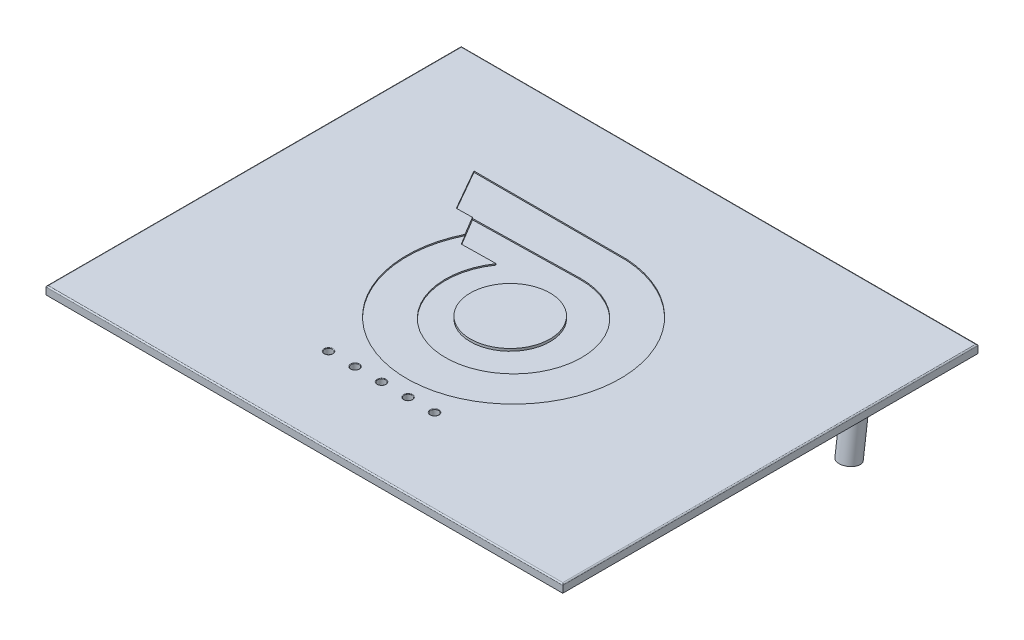
SolidWorks part; units mm, degrees
ref_plane "Front Plane" through (0, 0, 0) normal (0, 0, 1) x (1, 0, 0)
ref_plane "Top Plane" through (0, 0, 0) normal (0, 1, 0) x (1, 0, 0)
ref_plane "Right Plane" through (0, 0, 0) normal (1, 0, 0) x (0, 0, -1)
sketch "Sketch1" plane through (0, 0, 0) normal (0, 1, 0) x (1, 0, 0)
  line L1 (-64, -50.5) -> (64, -50.5)
  line L2 (-64, -50.5) -> (-64, 50.5)
  line L3 (-64, 50.5) -> (64, 50.5)
  line L4 (64, -50.5) -> (64, 50.5)
  line L5 (-64, -50.5) -> (64, 50.5) construction
  line L6 (-64, 50.5) -> (64, -50.5) construction
  point P0 (0, 0)
  dimension "D1" = 101
  dimension "D2" = 128
extrude "Boss-Extrude1" add sketch "Sketch1" along normal blind 2
sketch "Sketch2" plane through (0, 0, 0) normal (0, -1, 0) x (1, 0, 0)
  line L0 (-64, 49) -> (-62.9, 49) construction
  line L1 (-64, 50.5) -> (64, 50.5) construction
  line L2 (64, 49) -> (62.9, 49) construction
  line L3 (64, -50.5) -> (-64, -50.5) construction
  line L4 (62.9, 49) -> (61.7, 49)
  line L5 (62.9, 49) -> (62.9, -49)
  line L6 (62.9, -49) -> (61.7, -49)
  line L7 (61.7, 49) -> (61.7, -49)
  line L8 (-64, -51.87) -> (-64, 50.98) construction
  line L9 (-62.9, 49) -> (-61.7, 49)
  line L10 (-62.9, 49) -> (-62.9, -49)
  line L11 (-62.9, -49) -> (-61.7, -49)
  line L12 (-61.7, 49) -> (-61.7, -49)
  line L13 (-62.9, 49) -> (-62.9, 50.5) construction
  line L14 (64, 50.98) -> (64, -51.87) construction
  dimension "D1" = 1.1
  dimension "D2" = 1.1
  dimension "D3" = 1.2
  dimension "D4" = 1.2
  dimension "D5" = 1.5
  dimension "D6" = 1.5
  dimension "D7" = 1.5
  dimension "D8" = 1.5
extrude "Boss-Extrude2" add sketch "Sketch2" along normal blind 1
sketch "Sketch3" plane through (0, 0, 50.5) normal (0, 0, 1) x (1, 0, 0)
  line L1 (-64, 2) -> (64, 2)
  line L2 (-64, 2) -> (-64, 0)
  line L3 (-64, 0) -> (64, 0)
  line L4 (64, 2) -> (64, 0)
extrude "Boss-Extrude3" add sketch "Sketch3" along normal blind 0.48
sketch "Sketch4" plane through (0, 0, -50.5) normal (0, 0, -1) x (-1, 0, 0)
  line L1 (-64, 2) -> (64, 2)
  line L2 (-64, 2) -> (-64, 0)
  line L3 (-64, 0) -> (64, 0)
  line L4 (64, 2) -> (64, 0)
extrude "Boss-Extrude4" add sketch "Sketch4" along normal blind 1.37
sketch "Sketch5" plane through (0, -10.49, 1.3637) normal (0, 0.9917, -0.1289) x (1, 0, 0)
  circle A1 centre (-59.4789, 26.4337) radius 2.5 construction
  circle A3 centre (-59.4789, 26.4337) radius 2.5
  circle A5 centre (58.8211, 26.4337) radius 2.5 construction
  circle A7 centre (58.8211, 26.4337) radius 2.5
extrude "Boss-Extrude5" add sketch "Sketch5" along normal blind 13 from offset 2
hole_wizard "M3 Clearance Hole1" positions "Sketch7" profile "Sketch6" hole size "M3" standard "ANSI Metric"
sketch "Sketch7" plane through (0, -8.5067, 1.1059) normal (0, -0.9917, 0.1289) x (1, 0, 0)
  circle A1 centre (58.8211, -26.4337) radius 2.5 construction
  point P0 (58.8211, -26.4337)
  point P10 (58.8211, -26.4337)
sketch "Sketch6" plane through (58.8211, -11.9144, -25.1072) normal (1, 0, 0) x (0, -0.1289, -0.9917)
  line L0 (0, 0) -> (0, 10.7811)
  line L1 (0, 10.7811) -> (1.3, 10)
  line L2 (1.3, 10) -> (1.3, 0.2)
  line L3 (1.3, 0.2) -> (1.5, 0)
  line L5 (1.5, 0) -> (0, 0)
  line L6 (-1.3, 0.2) -> (-1.5, 0) construction
  line L10 (0, 10.7811) -> (-1.3, 10) construction
  line L11 (0, -6.35) -> (0, 107.95) construction
  dimension "Hole Dia." = 2.6
  dimension "Hole Depth" = 10
  dimension "Near C'Sink Dia." = 3
  dimension "Near C'Sink Angle" = 90
  dimension "Drill Angle" = 118
hole_wizard "M3 Clearance Hole2" positions "Sketch9" profile "Sketch8" hole size "M3" standard "ANSI Metric"
sketch "Sketch9" plane through (0, -8.5067, 1.1059) normal (0, -0.9917, 0.1289) x (1, 0, 0)
  circle A0 centre (-59.4789, -26.4337) radius 2.5 construction
  circle A1 centre (-59.4789, -26.4337) radius 2.5 construction
  point P0 (-59.4789, -26.4337)
sketch "Sketch8" plane through (-59.4789, -11.9144, -25.1072) normal (1, 0, 0) x (0, -0.1289, -0.9917)
  line L0 (0, 0) -> (0, 10.7811)
  line L1 (0, 10.7811) -> (1.3, 10)
  line L2 (1.3, 10) -> (1.3, 0.2)
  line L3 (1.3, 0.2) -> (1.5, 0)
  line L5 (1.5, 0) -> (0, 0)
  line L6 (-1.3, 0.2) -> (-1.5, 0) construction
  line L10 (0, 10.7811) -> (-1.3, 10) construction
  line L11 (0, -6.35) -> (0, 107.95) construction
  dimension "Hole Dia." = 2.6
  dimension "Hole Depth" = 10
  dimension "Near C'Sink Dia." = 3
  dimension "Near C'Sink Angle" = 90
  dimension "Drill Angle" = 118
ref_plane "Plane1" through (-21.0589, -2.7915, 45.8445) normal (1, 0, 0) x (0, 0, -1)
ref_plane "Plane2" through (17.4411, -2.7928, 45.8346) normal (0, -0.9917, 0.1289) x (-1, 0, 0)
sketch "Sketch13" plane through (0, -8.9034, 1.1574) normal (0, 0.9917, -0.1289) x (1, 0, 0)
  line L0 (-21.0589, -45.1021) -> (17.4411, -45.1021) construction
  line L1 (-21.0589, -45.1021) -> (17.4411, -45.1021)
sketch "Sketch14" plane through (0, 0, 0) normal (0, -1, 0) x (1, 0, 0)
  line L0 (-21.0589, 35.257) -> (-21.0589, 56.432) construction
  line L2 (17.4411, 31.0543) -> (17.4411, 29.0543) construction
  line L3 (17.4411, 29.0543) -> (-21.0589, 29.0543) construction
  line L4 (-21.0589, 31.0543) -> (-21.0589, 29.0543) construction
  line L7 (-15.3761, 31.0543) -> (-15.3761, 29.0543) construction
  line L8 (-15.3761, 29.0543) -> (-14.4954, 29.0543) construction
  line L9 (-14.4954, 31.0543) -> (-14.4954, 29.0543) construction
  line L10 (-8.8127, 31.0543) -> (-8.8127, 29.0543) construction
  line L11 (-8.8127, 29.0543) -> (-7.9319, 29.0543) construction
  line L12 (-7.9319, 31.0543) -> (-7.9319, 29.0543) construction
  line L14 (10.8777, 31.0543) -> (10.8777, 29.0543) construction
  line L15 (10.8777, 29.0543) -> (11.7584, 29.0543) construction
  line L16 (11.7584, 31.0543) -> (11.7584, 29.0543) construction
  line L18 (4.3142, 31.0543) -> (4.3142, 29.0543) construction
  line L19 (4.3142, 29.0543) -> (5.195, 29.0543) construction
  line L20 (5.195, 31.0543) -> (5.195, 29.0543) construction
  line L21 (-21.0589, 31.0543) -> (-15.3761, 31.0543) construction
  line L22 (-15.3761, 31.0543) -> (-14.4954, 31.0543) construction
  line L23 (-14.4954, 31.0543) -> (-8.8127, 31.0543) construction
  line L24 (-7.9319, 31.0543) -> (-8.8127, 31.0543) construction
  line L25 (-7.9319, 31.0543) -> (-2.2492, 31.0543) construction
  line L26 (5.195, 31.0543) -> (4.3142, 31.0543) construction
  line L27 (5.195, 31.0543) -> (10.8777, 31.0543) construction
  line L28 (10.8777, 31.0543) -> (11.7584, 31.0543) construction
  line L29 (11.7584, 31.0543) -> (17.4411, 31.0543) construction
  line L30 (-15.3761, 31.0543) -> (-14.4954, 29.0543) construction
  line L31 (-8.8127, 31.0543) -> (-7.9319, 29.0543) construction
  line L32 (4.3142, 31.0543) -> (5.195, 29.0543) construction
  line L33 (10.8777, 31.0543) -> (11.7584, 29.0543) construction
  line L34 (-21.0589, 30.0543) -> (17.4411, 30.0543) construction
  line L35 (-2.2492, 31.0543) -> (-2.2492, 29.0543) construction
  line L36 (-1.3685, 31.0543) -> (-1.3685, 29.0543) construction
  line L37 (-1.3685, 31.0543) -> (-2.2492, 31.0543) construction
  line L38 (-2.2492, 31.0543) -> (-1.3685, 29.0543) construction
  line L39 (-1.3685, 31.0543) -> (4.3142, 31.0543) construction
  circle A1 centre (-8.3723, 30.0543) radius 1
  circle A2 centre (4.7546, 30.0543) radius 1
  circle A3 centre (11.3181, 30.0543) radius 1
  circle A4 centre (-14.9358, 30.0543) radius 1
  circle A5 centre (-1.8089, 30.0543) radius 1
  point P25 (-15.3761, 31.0543)
  dimension "D1" = 2
  dimension "D2" = 38.5
sketch "Sketch15" plane through (0, 0, 0) normal (0, -1, 0) x (1, 0, 0)
  line L0 (-16.4315, 32.0543) -> (-14.9358, 30.0543) construction
  line L1 (-16.4315, 32.0543) -> (14.7611, 32.0543)
  line L3 (-16.4315, 28.0543) -> (14.7611, 28.0543)
  line L5 (14.7611, 28.0543) -> (19.7611, 28.0543)
  line L7 (14.7611, 32.0543) -> (19.7611, 32.0543)
  line L8 (19.7611, 28.0543) -> (19.7611, 32.0543)
  line L9 (-16.4315, 32.0543) -> (-21.4315, 32.0543)
  line L11 (-16.4315, 28.0543) -> (-21.4315, 28.0543)
  line L12 (-21.4315, 32.0543) -> (-21.4315, 28.0543)
  line L13 (-14.9358, 30.0543) -> (-16.4315, 28.0543) construction
  line L14 (-16.4315, 32.0543) -> (-16.4315, 28.0543) construction
  line L15 (-21.4315, 30.0543) -> (19.7611, 30.0543) construction
  circle A0 centre (11.3181, 30.0543) radius 1 construction
  circle A1 centre (4.7546, 30.0543) radius 1 construction
  circle A2 centre (-8.3723, 30.0543) radius 1 construction
  circle A3 centre (-14.9358, 30.0543) radius 1 construction
  circle A4 centre (11.3181, 30.0543) radius 1 construction
  circle A5 centre (4.7546, 30.0543) radius 1 construction
  circle A6 centre (-8.3723, 30.0543) radius 1 construction
  circle A7 centre (-14.9358, 30.0543) radius 1 construction
  dimension "D1" = 5
  dimension "D2" = 5
  dimension "D3" = 4
extrude "Cut-Extrude1" cut sketch "Sketch14" against normal blind 5
extrude "Cut-Extrude2" cut sketch "Sketch15" against normal blind 0.4
sketch "Sketch28" plane through (0, 2, 0) normal (0, 1, 0) x (1, 0, 0)
  line L0 (-105.9112, 39.4438) -> (44.0888, 39.4438) construction
  line L13 (-35.5896, 26.6111) -> (2.3582, 26.6111)
  line L14 (-35.5896, 26.6111) -> (-29.7648, 16.4235)
  line L15 (-29.7648, 16.4235) -> (-20.1685, 16.5748)
  line L16 (-25.8891, 16.5492) -> (-21.7753, 9.6578)
  line L17 (-21.7753, 9.6578) -> (-13.2552, 9.7921)
  line L18 (-25.8891, 16.5492) -> (0.2164, 17.0688)
  circle A7 centre (0, 0) radius 9.8716
  arc A8 (-20.1685, 16.5748) -> (2.3582, 26.6111) centre (0.6217, 0.2096) ccw
  arc A9 (-13.2552, 9.7921) -> (0.2164, 17.0688) centre (0.6217, 0.2096) ccw
sketch "Sketch31" plane through (0, 2, 0) normal (0, 1, 0) x (1, 0, 0)
  line L0 (-35.5896, 26.6111) -> (2.3582, 26.6111) construction
  line L1 (-35.5896, 26.6111) -> (-29.7648, 16.4235) construction
  line L2 (-29.7648, 16.4235) -> (-20.1685, 16.5748) construction
  line L3 (-35.5896, 26.6111) -> (2.3582, 26.6111)
  line L4 (-35.5896, 26.6111) -> (-29.7648, 16.4235)
  line L5 (-29.7648, 16.4235) -> (-20.1685, 16.5748)
  arc A0 (-20.1685, 16.5748) -> (2.3582, 26.6111) centre (0.6217, 0.2096) ccw construction
  arc A1 (-20.1685, 16.5748) -> (2.3582, 26.6111) centre (0.6217, 0.2096) ccw
sketch "Sketch29" plane through (0, 2, 0) normal (0, 1, 0) x (1, 0, 0)
  line L0 (-25.8891, 16.5492) -> (0.2164, 17.0688) construction
  line L1 (-25.8891, 16.5492) -> (-21.7753, 9.6578) construction
  line L2 (-21.7753, 9.6578) -> (-13.2552, 9.7921) construction
  line L3 (-25.8891, 16.5492) -> (0.2164, 17.0688)
  line L4 (-25.8891, 16.5492) -> (-21.7753, 9.6578)
  line L5 (-21.7753, 9.6578) -> (-13.2552, 9.7921)
  arc A0 (-13.2552, 9.7921) -> (0.2164, 17.0688) centre (0.6217, 0.2096) ccw construction
  arc A1 (-13.2552, 9.7921) -> (0.2164, 17.0688) centre (0.6217, 0.2096) ccw
sketch "Sketch30" plane through (0, 2, 0) normal (0, 1, 0) x (1, 0, 0)
  circle A0 centre (0, 0) radius 9.8716 construction
  circle A1 centre (0, 0) radius 9.8716
extrude "Cut-Extrude4" cut sketch "Sketch31" against normal blind 0.3
extrude "Cut-Extrude5" cut sketch "Sketch29" against normal blind 0.6
extrude "Boss-Extrude13" add sketch "Sketch30" against normal blind 0.6 separate body
fillet "Fillet1" radius 0.3 4 edges at (64, 2, -0.445) (0, 2, -51.87) (-64, 2, -0.445) (0, 2, 50.98)
fillet "Fillet2" radius 0.12 10 edges at (11.3181, 0.4, 29.0543) (11.3181, 2, 29.0543) (4.7546, 0.4, 29.0543) (4.7546, 2, 29.0543) (-1.8089, 0.4, 29.0543) (-1.8089, 2, 29.0543) (-8.3723, 0.4, 29.0543) (-8.3723, 2, 29.0543) (-14.9358, 0.4, 29.0543) (-14.9358, 2, 29.0543)
